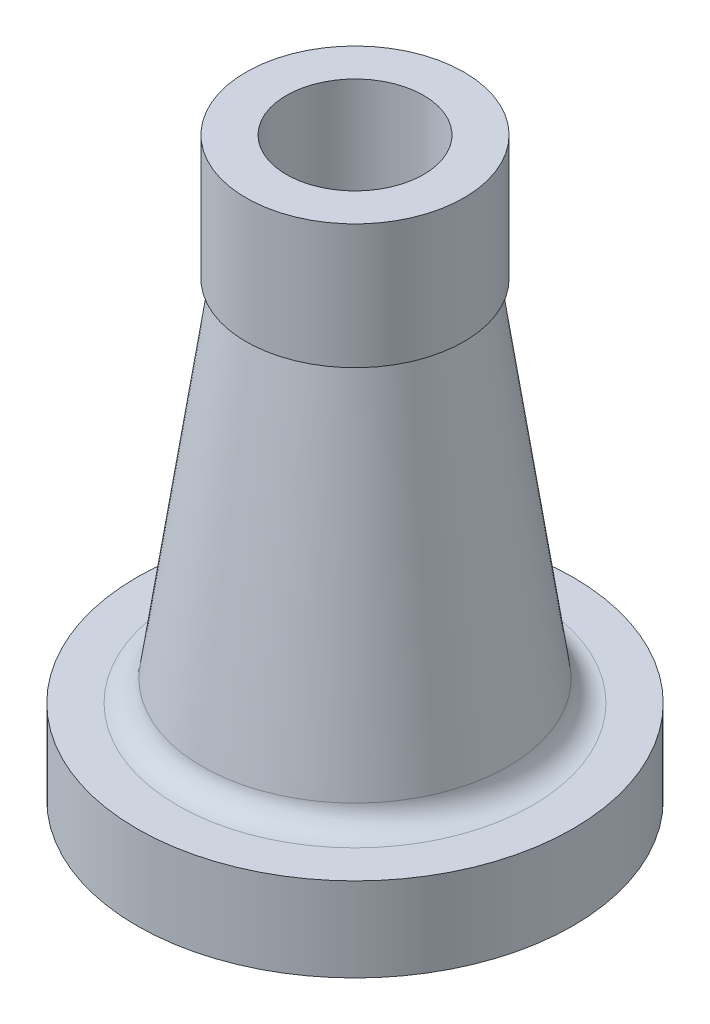
SolidWorks part; units mm, degrees
ref_plane "Front Plane" through (0, 0, 0) normal (0, 0, 1) x (1, 0, 0)
ref_plane "Top Plane" through (0, 0, 0) normal (0, 1, 0) x (1, 0, 0)
ref_plane "Right Plane" through (0, 0, 0) normal (1, 0, 0) x (0, 0, -1)
sketch "Sketch1" plane through (0, 0, 0) normal (0, 0, 1) x (1, 0, 0)
  line L0 (0, 0) -> (0, 161.6382) construction
  line L1 (-70, 0) -> (-70, 27)
  line L2 (-70, 27) -> (-57, 27)
  line L3 (-49.0825, 33.8544) -> (-33, 145)
  line L4 (-33, 145) -> (-35, 145)
  line L5 (-35, 145) -> (-35, 185)
  line L6 (-35, 185) -> (-22.0351, 185)
  line L7 (-22.0351, 185) -> (-22.0351, 130)
  line L8 (-22.0351, 130) -> (-40.4116, 3)
  line L9 (-40.4116, 3) -> (-50, 3)
  line L10 (-50, 3) -> (-50, 0)
  line L11 (-50, 0) -> (-70, 0)
  arc A0 (-57, 27) -> (-49.0825, 33.8544) centre (-57, 35) ccw
  dimension "D6" = 8
  dimension "D1" = 185
  dimension "D2" = 27
  dimension "D3" = 35
  dimension "D4" = 50
  dimension "D5" = 70
  dimension "D7" = 57
  dimension "D8" = 40
  dimension "D9" = 13
  dimension "D10" = 3
  dimension "D11" = 33
  dimension "D12" = 130
revolve "Revolve1" add sketch "Sketch1" angle 360 about L0
